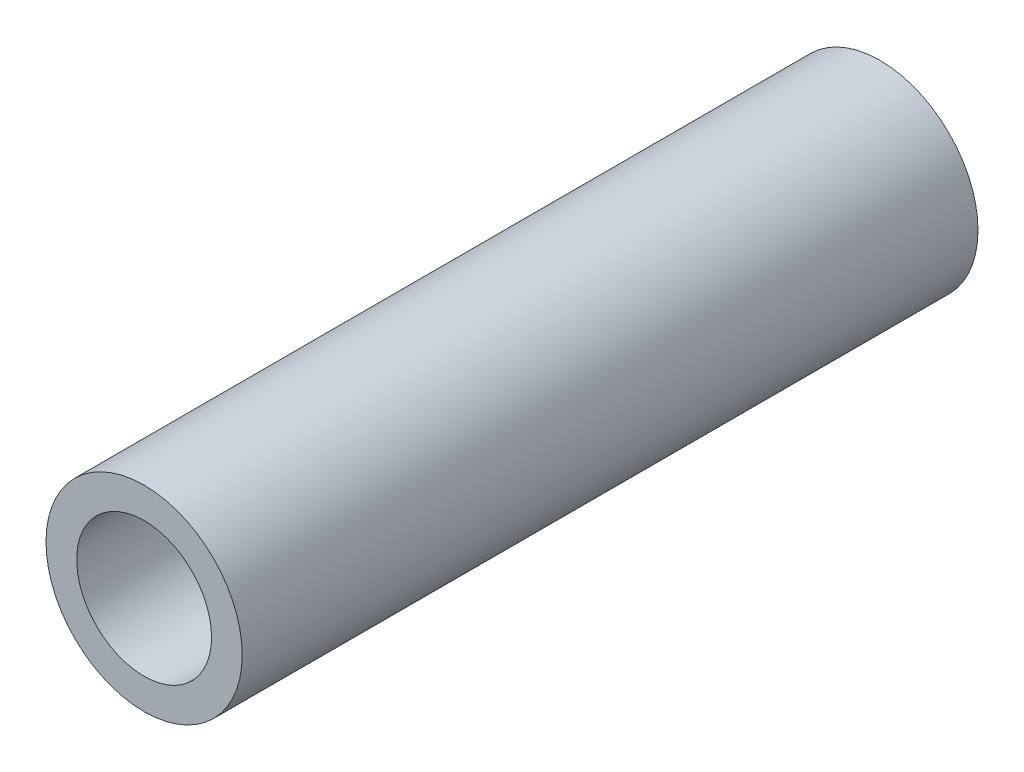
SolidWorks part; units mm, degrees
ref_plane "Płaszczyzna przednia" through (0, 0, 0) normal (0, 0, 1) x (1, 0, 0)
ref_plane "Płaszczyzna górna" through (0, 0, 0) normal (0, 1, 0) x (1, 0, 0)
ref_plane "Płaszczyzna prawa" through (0, 0, 0) normal (1, 0, 0) x (0, 0, -1)
sketch "Szkic1" plane through (0, 0, 0) normal (0, 0, 1) x (1, 0, 0)
  circle A0 centre (0, 0) radius 5.5
  circle A1 centre (0, 0) radius 8
  dimension "D1" = 11
  dimension "D2" = 16
extrude "Dodanie-wyciągnięcie1" add sketch "Szkic1" against normal blind 60
